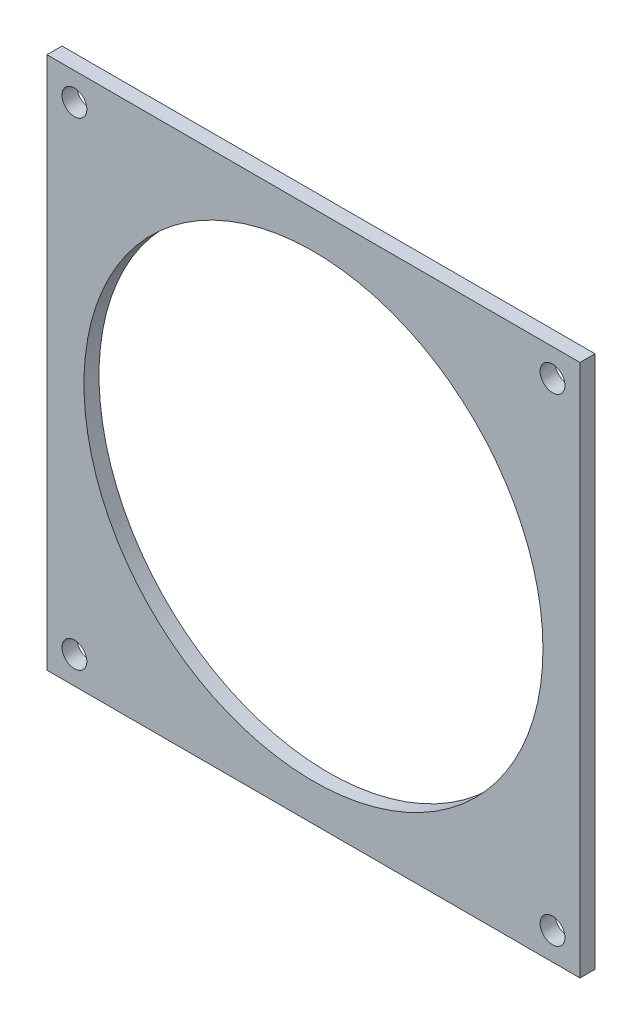
SolidWorks part; units mm, degrees
material "Acrylic (Medium-high impact)"
ref_plane "Front Plane" through (0, 0, 0) normal (0, 0, 1) x (1, 0, 0)
ref_plane "Top Plane" through (0, 0, 0) normal (0, 1, 0) x (1, 0, 0)
ref_plane "Right Plane" through (0, 0, 0) normal (1, 0, 0) x (0, 0, -1)
sketch "Sketch1" plane through (0, 0, 0) normal (0, 0, 1) x (1, 0, 0)
  line L0 (167.875, 167.875) -> (9.125, 9.125) construction
  line L1 (0, 0) -> (177, 0)
  line L2 (0, 0) -> (0, 177)
  line L3 (0, 177) -> (177, 177)
  line L4 (177, 0) -> (177, 177)
  line L5 (9.125, 9.125) -> (167.875, 9.125) construction
  line L6 (9.125, 9.125) -> (9.125, 167.875) construction
  line L7 (9.125, 167.875) -> (167.875, 167.875) construction
  line L8 (167.875, 9.125) -> (167.875, 167.875) construction
  line L9 (5, 9.125) -> (0, 9.125) construction
  line L10 (163.6459, 1.8) -> (159.4168, 9.125)
  line L11 (17.5832, 9.125) -> (13.3541, 16.45)
  line L12 (13.3541, 16.45) -> (4.8959, 16.45)
  line L13 (4.8959, 16.45) -> (0.6668, 9.125)
  line L14 (0.6668, 9.125) -> (4.8959, 1.8)
  line L15 (4.8959, 1.8) -> (13.3541, 1.8)
  line L16 (13.3541, 1.8) -> (17.5832, 9.125)
  line L17 (172.1041, 1.8) -> (163.6459, 1.8)
  line L18 (176.3332, 9.125) -> (172.1041, 1.8)
  line L19 (172.1041, 16.45) -> (176.3332, 9.125)
  line L20 (9.125, 88.5) -> (0, 88.5) construction
  line L21 (88.5, 9.125) -> (88.5, 0) construction
  line L22 (163.6459, 16.45) -> (172.1041, 16.45)
  line L23 (159.4168, 9.125) -> (163.6459, 16.45)
  line L24 (172.1041, 160.55) -> (176.3332, 167.875)
  line L25 (176.3332, 167.875) -> (172.1041, 175.2)
  line L26 (172.1041, 175.2) -> (163.6459, 175.2)
  line L27 (163.6459, 175.2) -> (159.4168, 167.875)
  line L28 (159.4168, 167.875) -> (163.6459, 160.55)
  line L29 (163.6459, 160.55) -> (172.1041, 160.55)
  line L30 (4.8959, 160.55) -> (0.6668, 167.875)
  line L31 (0.6668, 167.875) -> (4.8959, 175.2)
  line L32 (4.8959, 175.2) -> (13.3541, 175.2)
  line L33 (13.3541, 175.2) -> (17.5832, 167.875)
  line L34 (17.5832, 167.875) -> (13.3541, 160.55)
  line L35 (13.3541, 160.55) -> (4.8959, 160.55)
  circle A0 centre (9.125, 9.125) radius 4.125
  circle A1 centre (9.125, 9.125) radius 7.325 construction
  circle A2 centre (167.875, 9.125) radius 4.125
  circle A3 centre (167.875, 167.875) radius 4.125
  circle A4 centre (88.5, 88.5) radius 76.2
  circle A5 centre (9.125, 167.875) radius 4.125
  text T0 "                 Base Plate" font "Century Gothic" height 1.5
  point P47 (88.5, 167.875)
  dimension "D2" = 8.25
  dimension "D3" = 5
  dimension "D4" = 152.4
  dimension "D1" = 158.75
  dimension "D5" = 14.65
extrude "Boss-Extrude1" add sketch "Sketch1" along normal blind 5 contours L1 L4 L3 L2 A4 L10 L23 L22 L19 L18 L17 L16 L15 L14 L13 L12 L11 L29 L28 L27 L26 L25 L24 L34 L35 L30 L31 L32 L33 | L35 L34 L33 L32 L31 L30 A5 | L15 L16 L11 L12 L13 L14 A0 | L23 L10 L17 L18 L19 L22 A2 | L28 L29 L24 L25 L26 L27 A3
